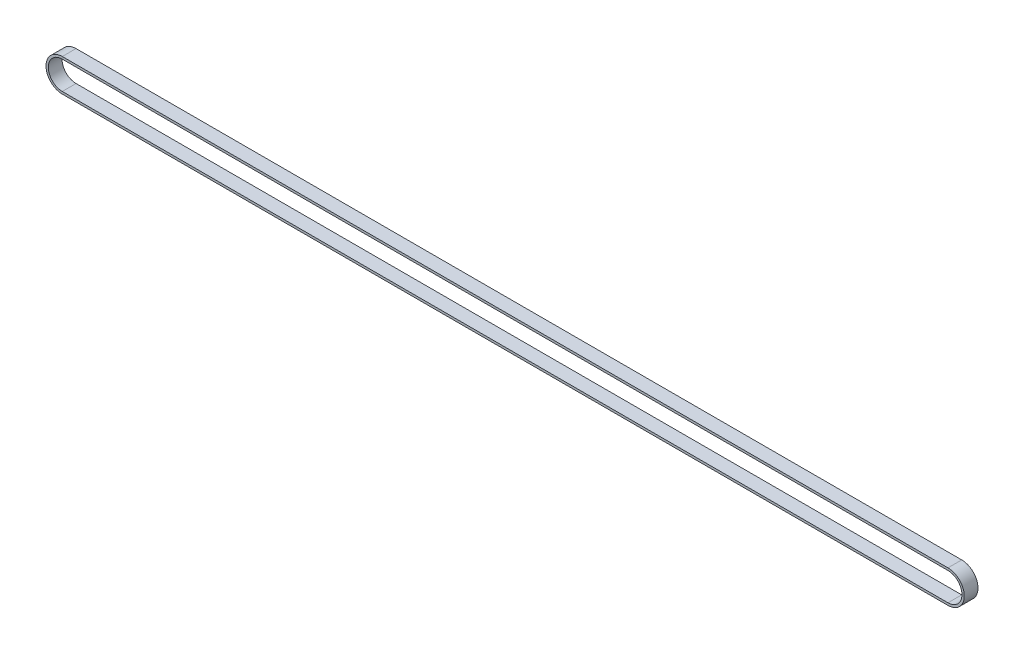
SolidWorks part; units mm, degrees
ref_plane "Front Plane" through (0, 0, 0) normal (0, 0, 1) x (1, 0, 0)
ref_plane "Top Plane" through (0, 0, 0) normal (0, 1, 0) x (1, 0, 0)
ref_plane "Right Plane" through (0, 0, 0) normal (1, 0, 0) x (0, 0, -1)
sketch "Sketch2" plane through (0, 0, 0) normal (0, 0, 1) x (1, 0, 0)
  line L0 (193.13, -6.1) -> (0, -6.1)
  line L1 (0, 6.1) -> (193.13, 6.1)
  line L2 (193.13, 6.1) -> (193.13, -6.1) construction
  arc A0 (0, -6.1) -> (0, 6.1) centre (0, 0) cw
  dimension "D1" = 6.1
  dimension "D2" = 193.13
extrude "Extrude-Thin1" add sketch "Sketch2" along normal blind 6 thin thin type one direction reverse wall 1
mirror "Mirror1" about plane through (193.13, 7.1, 6) normal (1, 0, 0) of "Extrude-Thin1"
equation "\"D2@Sketch2\"= 386.26 / 2"
